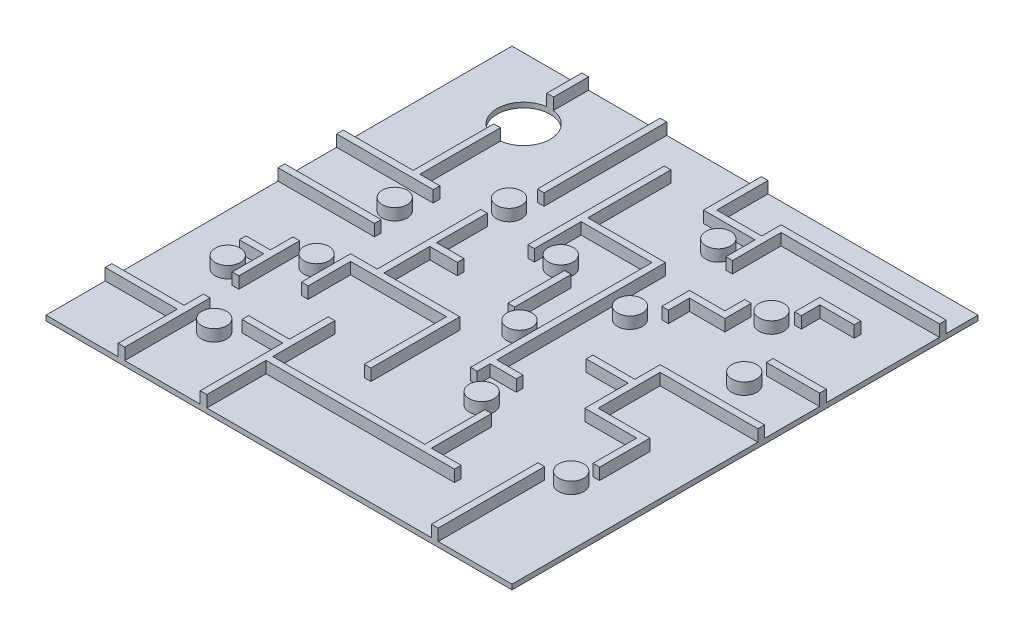
SolidWorks part; units mm, degrees
ref_plane "Front Plane" through (0, 0, 0) normal (0, 0, 1) x (1, 0, 0)
ref_plane "Top Plane" through (0, 0, 0) normal (0, 1, 0) x (1, 0, 0)
ref_plane "Right Plane" through (0, 0, 0) normal (1, 0, 0) x (0, 0, -1)
sketch "Sketch1" plane through (0, 0, 0) normal (0, 1, 0) x (1, 0, 0)
  line L1 (140, -140) -> (-140, -140)
  line L2 (140, -140) -> (140, 140)
  line L3 (140, 140) -> (-140, 140)
  line L4 (-140, -140) -> (-140, 140)
  line L5 (140, -140) -> (-140, 140) construction
  line L6 (140, 140) -> (-140, -140) construction
  circle A0 centre (-96, 103) radius 12.5 construction
  circle A2 centre (-96, 103) radius 16
  point P0 (0, 0)
  dimension "D2" = 25
  dimension "D4" = 44
  dimension "D5" = 37
  dimension "D3" = 32
  dimension "D1" = 280
extrude "Boss-Extrude1" add sketch "Sketch1" along normal mid plane 3
sketch "Sketch2" plane through (0, 1.5, 0) normal (0, 1, 0) x (1, 0, 0)
  line L0 (-139.5466, -22.5168) -> (140.7215, -22.5168) construction
  line L1 (-51, 140) -> (-51, 66.2868)
  line L5 (-140, 140) -> (-140, -140)
  line L6 (-140, -140) -> (140, -140)
  line L7 (140, -140) -> (140, 140)
  line L8 (140, 140) -> (-140, 140)
  line L9 (-140, 140) -> (-140, -140) construction
  line L10 (-140, -140) -> (140, -140) construction
  line L11 (140, -140) -> (140, 140) construction
  line L12 (140, 140) -> (-140, 140) construction
  line L14 (-82, 34.6244) -> (-82, 3.4233) construction
  line L16 (-94, 140) -> (-98, 140)
  line L17 (-94, 140) -> (-94, 118.8745)
  line L19 (-98, 140) -> (-98, 118.8745)
  line L20 (-94, 140) -> (-98, 118.8745) construction
  line L21 (-94, 118.8745) -> (-98, 140) construction
  line L22 (-51, 66.2868) -> (-47, 66.2868)
  line L25 (-47, 66.2868) -> (-47, 140)
  line L26 (-47, 140) -> (-51, 140)
  line L27 (-140, 38.6244) -> (-98, 38.6244)
  line L29 (-98, 38.6244) -> (-98, 87.1255)
  line L31 (-94, 38.6244) -> (-94, 87.1255)
  line L32 (-98, 38.6244) -> (-94, 87.1255) construction
  line L33 (-98, 87.1255) -> (-94, 38.6244) construction
  line L34 (-94, 38.6244) -> (-82, 38.6244)
  line L35 (-82, 38.6244) -> (-82, 34.6244)
  line L36 (-82, 34.6244) -> (-140, 34.6244)
  line L37 (-140, 34.6244) -> (-140, 38.6244)
  line L38 (-140, -100.4184) -> (-96.6685, -100.4184)
  line L39 (-140, 3.4233) -> (-82, 3.4233)
  line L40 (-140, 3.4233) -> (-140, -0.5767)
  line L41 (-140, -0.5767) -> (-82, -0.5767)
  line L42 (-82, 3.4233) -> (-82, -0.5767)
  line L43 (-96.6685, -100.4184) -> (-96.6685, -88.7386)
  line L44 (-96.6685, -88.7386) -> (-92.6685, -88.7386)
  line L45 (-92.6685, -88.7386) -> (-92.6685, -140)
  line L46 (-92.6685, -140) -> (-96.6685, -140)
  line L47 (-96.6685, -140) -> (-96.6685, -104.4184)
  line L48 (-96.6685, -104.4184) -> (-140, -104.4184)
  line L49 (-140, -104.4184) -> (-140, -100.4184)
  line L50 (-47.3451, -140) -> (-47.3451, -90.3646)
  line L51 (-47.3451, -90.3646) -> (-71.8819, -90.3646)
  line L52 (-71.8819, -90.3646) -> (-71.8819, -86.3646)
  line L53 (-71.8819, -86.3646) -> (-47.3451, -86.3646)
  line L54 (-47.3451, -86.3646) -> (-47.3451, -63.0886)
  line L55 (-47.3451, -63.0886) -> (-43.3451, -63.0886)
  line L56 (-43.3451, -63.0886) -> (-43.3451, -100.4184)
  line L57 (-43.3451, -100.4184) -> (48.0278, -100.4184)
  line L58 (48.0278, -100.4184) -> (48.0278, -64.3719)
  line L59 (48.0278, -64.3719) -> (52.0278, -64.3719)
  line L60 (52.0278, -64.3719) -> (52.0278, -100.4184)
  line L61 (52.0278, -100.4184) -> (69.8279, -100.4184)
  line L62 (69.8279, -100.4184) -> (69.8279, -104.4184)
  line L63 (69.8279, -104.4184) -> (-43.3451, -104.4184)
  line L64 (-43.3451, -104.4184) -> (-43.3451, -140)
  line L65 (-43.3451, -140) -> (-47.3451, -140)
  line L66 (140, 7.7373) -> (81.2931, 7.7373)
  line L67 (91.6226, -76) -> (95.6226, -76)
  line L68 (91.6226, -76) -> (91.6226, -140)
  line L69 (91.6226, -140) -> (95.6226, -140)
  line L70 (95.6226, -76) -> (95.6226, -140)
  line L71 (81.2931, 7.7373) -> (81.2931, -29.5435)
  line L72 (81.2931, -29.5435) -> (112.4312, -29.5435)
  line L73 (112.4312, -29.5435) -> (112.4312, -59.7773)
  line L74 (112.4312, -59.7773) -> (108.4312, -59.7773)
  line L75 (108.4312, -59.7773) -> (108.4312, -33.5435)
  line L76 (108.4312, -33.5435) -> (77.2931, -33.5435)
  line L77 (77.2931, -33.5435) -> (77.2931, -7.4768)
  line L78 (77.2931, -7.4768) -> (52.0278, -7.4768)
  line L79 (52.0278, -7.4768) -> (52.0278, -3.4768)
  line L80 (52.0278, -3.4768) -> (77.2931, -3.4768)
  line L81 (77.2931, -3.4768) -> (77.2931, 11.7373)
  line L82 (77.2931, 11.7373) -> (140, 11.7373)
  line L83 (140, 11.7373) -> (140, 7.7373)
  line L84 (-99.5107, -32.1119) -> (-95.5107, -32.1119)
  line L85 (140, 48.844) -> (108, 48.844)
  line L86 (140, 48.844) -> (140, 44.844)
  line L87 (140, 44.844) -> (108, 44.844)
  line L88 (108, 48.844) -> (108, 44.844)
  line L89 (-95.5107, -32.1119) -> (-95.5107, -68.5942)
  line L90 (-95.5107, -68.5942) -> (-99.5107, -68.5942)
  line L91 (-99.5107, -68.5942) -> (-99.5107, -49.6758)
  line L92 (-99.5107, -49.6758) -> (-114.1271, -49.6758)
  line L93 (-114.1271, -49.6758) -> (-114.1271, -45.6758)
  line L94 (-114.1271, -45.6758) -> (-99.5107, -45.6758)
  line L95 (-99.5107, -45.6758) -> (-99.5107, -32.1119)
  line L96 (-73.4352, -53.0425) -> (-69.4352, -53.0425)
  line L97 (-69.4352, -53.0425) -> (-69.4352, -27.5282)
  line L98 (-69.4352, -27.5282) -> (-11.8371, -27.5282)
  line L99 (-11.8371, -27.5282) -> (-11.8371, -76.9197)
  line L100 (-11.8371, -76.9197) -> (-7.8371, -76.9197)
  line L101 (-7.8371, -76.9197) -> (-7.8371, -23.5282)
  line L102 (-7.8371, -23.5282) -> (-53.4401, -23.5282)
  line L103 (-53.4401, -23.5282) -> (-53.4401, 4.0431)
  line L104 (-53.4401, 4.0431) -> (-36.8827, 4.0431)
  line L105 (-36.8827, 4.0431) -> (-36.8827, 8.0431)
  line L106 (-36.8827, 8.0431) -> (-53.4401, 8.0431)
  line L107 (-53.4401, 8.0431) -> (-53.4401, 38.6312)
  line L108 (-53.4401, 38.6312) -> (-57.4401, 38.6312)
  line L109 (-57.4401, 38.6312) -> (-57.4401, -23.5282)
  line L110 (-57.4401, -23.5282) -> (-73.4352, -23.5282)
  line L111 (-73.4352, -23.5282) -> (-73.4352, -53.0425)
  line L112 (114.8331, 94.8013) -> (114.8331, 90.8013)
  line L113 (-0.421, 32.0095) -> (3.579, 32.0095)
  line L114 (-0.421, 32.0095) -> (-0.421, -1.9905)
  line L115 (-0.421, -1.9905) -> (3.579, -1.9905)
  line L116 (3.579, 32.0095) -> (3.579, -1.9905)
  line L117 (114.8331, 90.8013) -> (94.2035, 90.8013)
  line L118 (94.2035, 90.8013) -> (94.2035, 79.6255)
  line L119 (94.2035, 79.6255) -> (90.2035, 79.6255)
  line L120 (90.2035, 79.6255) -> (90.2035, 94.8013)
  line L121 (90.2035, 94.8013) -> (114.8331, 94.8013)
  line L122 (68.7421, 71) -> (68.7421, 59.1986)
  line L123 (68.7421, 59.1986) -> (47.4471, 59.1986)
  line L124 (47.4471, 59.1986) -> (47.4471, 42.5547)
  line L125 (47.4471, 42.5547) -> (51.4471, 42.5547)
  line L126 (51.4471, 42.5547) -> (51.4471, 55.1986)
  line L127 (51.4471, 55.1986) -> (72.7421, 55.1986)
  line L128 (72.7421, 55.1986) -> (72.7421, 71)
  line L129 (72.7421, 71) -> (68.7421, 71)
  line L130 (21.7271, -46.6316) -> (25.7271, -46.6316)
  line L131 (25.7271, -46.6316) -> (25.7271, -38.8445)
  line L132 (25.7271, -38.8445) -> (41.4595, -38.8445)
  line L133 (41.4595, -38.8445) -> (41.4595, -34.8445)
  line L134 (41.4595, -34.8445) -> (25.7271, -34.8445)
  line L135 (25.7271, -34.8445) -> (25.7271, 66.4202)
  line L136 (25.7271, 66.4202) -> (-20.8726, 66.4202)
  line L137 (-20.8726, 66.4202) -> (-20.8726, 116.3442)
  line L138 (-20.8726, 116.3442) -> (-24.8726, 116.3442)
  line L139 (-24.8726, 116.3442) -> (-24.8726, 34.358)
  line L140 (-24.8726, 34.358) -> (-20.8726, 34.358)
  line L141 (-20.8726, 34.358) -> (-20.8726, 62.4202)
  line L142 (-20.8726, 62.4202) -> (21.7271, 62.4202)
  line L143 (21.7271, 62.4202) -> (21.7271, -46.6316)
  line L144 (140, 116.8451) -> (44.8417, 116.8451)
  line L145 (44.8417, 116.8451) -> (44.8417, 87.6566)
  line L146 (44.8417, 87.6566) -> (40.8417, 87.6566)
  line L147 (40.8417, 87.6566) -> (40.8417, 105.182)
  line L148 (40.8417, 105.182) -> (9.8488, 105.182)
  line L149 (9.8488, 105.182) -> (9.8488, 140)
  line L150 (9.8488, 140) -> (13.8488, 140)
  line L151 (13.8488, 140) -> (13.8488, 109.182)
  line L152 (13.8488, 109.182) -> (40.8417, 109.182)
  line L153 (40.8417, 109.182) -> (40.8417, 120.8451)
  line L154 (40.8417, 120.8451) -> (140, 120.8451)
  line L155 (140, 120.8451) -> (140, 116.8451)
  circle A0 centre (-96, 103) radius 16 construction
  circle A1 centre (-96, 103) radius 16 construction
  arc A4 (-94, 118.8745) -> (-98, 118.8745) centre (-96, 103) ccw
  arc A5 (-94, 87.1255) -> (-98, 87.1255) centre (-96, 103) cw
  circle A6 centre (-54.759, 52.9828) radius 7.5
  circle A7 centre (-89.4735, 19.0238) radius 7.5
  circle A8 centre (-83.7389, -33.6905) radius 7.5
  circle A9 centre (-109.5163, -61.2699) radius 7.5
  circle A10 centre (-80.6927, -98.2301) radius 7.5
  circle A12 centre (37.5874, -55.832) radius 7.5
  circle A13 centre (105.9105, -70.3332) radius 7.5
  circle A14 centre (11.8193, -7.3525) radius 7.5
  circle A15 centre (-9.7559, 39.067) radius 7.5
  circle A16 centre (29.1701, 94.8013) radius 7.5
  circle A17 centre (82.6249, 73.2846) radius 7.5
  circle A18 centre (37.5874, 33.2669) radius 7.5
  circle A19 centre (106.2527, 33.2879) radius 7.5
  point P9 (-82, 19.0238)
  point P14 (-96, 129.4373)
  point P21 (-96, 62.8749)
  point P66 (93.6226, -76)
  dimension "D6" = 29
  dimension "D8" = 15
  dimension "D52" = 15
  dimension "D53" = 15
  dimension "D54" = 15
  dimension "D55" = 15
  dimension "D57" = 15
  dimension "D58" = 15
  dimension "D59" = 15
  dimension "D60" = 15
  dimension "D61" = 15
  dimension "D62" = 15
  dimension "D63" = 15
  dimension "D64" = 15
  dimension "D1" = 0
  dimension "D3" = 4
  dimension "D4" = 4
  dimension "D9" = 4
  dimension "D10" = 4
  dimension "D11" = 58
  dimension "D12" = 4
  dimension "D13" = 58
  dimension "D14" = 4
  dimension "D15" = 4
  dimension "D16" = 4
  dimension "D17" = 4
  dimension "D18" = 4
  dimension "D19" = 4
  dimension "D20" = 4
  dimension "D21" = 4
  dimension "D22" = 64
  dimension "D23" = 4
  dimension "D24" = 4
  dimension "D25" = 4
  dimension "D26" = 4
  dimension "D27" = 4
  dimension "D28" = 4
  dimension "D29" = 32
  dimension "D30" = 4
  dimension "D31" = 4
  dimension "D32" = 4
  dimension "D33" = 4
  dimension "D34" = 4
  dimension "D35" = 4
  dimension "D36" = 4
  dimension "D37" = 4
  dimension "D38" = 34
  dimension "D39" = 4
  dimension "D40" = 4
  dimension "D41" = 4
  dimension "D42" = 4
  dimension "D43" = 4
  dimension "D44" = 4
  dimension "D45" = 4
  dimension "D46" = 4
  dimension "D47" = 4
  dimension "D48" = 4
  dimension "D49" = 4
  dimension "D50" = 4
  dimension "D51" = 4
extrude "Boss-Extrude2" add sketch "Sketch2" along normal blind 7
sketch "Sketch4" plane through (0, 1.5, 0) normal (0, 1, 0) x (1, 0, 0)
  line L0 (-98, 140) -> (-140, 140) construction
  line L1 (-103.2689, 140) -> (-87.6691, 140)
  line L2 (-103.2689, 140) -> (-103.2689, 109.252)
  line L3 (-103.2689, 109.252) -> (-87.6691, 109.252)
  line L4 (-87.6691, 140) -> (-87.6691, 109.252)
  line L5 (5.9631, 143.7406) -> (7.9794, 102.774)
  line L6 (-145.5082, 88.7508) -> (-75.5684, 88.7508)
  line L7 (-145.5082, 88.7508) -> (-145.5082, 30.0852)
  line L8 (-145.5082, 30.0852) -> (-75.5684, 30.0852)
  line L9 (-75.5684, 88.7508) -> (-75.5684, 30.0852)
  line L10 (-62.1484, 143.7406) -> (-36.1488, 143.7406)
  line L11 (-62.1484, 143.7406) -> (-62.1484, 63.1419)
  line L12 (-62.1484, 63.1419) -> (-36.1488, 63.1419)
  line L13 (-36.1488, 143.7406) -> (-36.1488, 63.1419)
  line L14 (-147.4549, 7.7999) -> (-80.2273, 7.7999)
  line L15 (-147.4549, 7.7999) -> (-147.4549, -3.3428)
  line L16 (-147.4549, -3.3428) -> (-80.2273, -3.3428)
  line L17 (-80.2273, 7.7999) -> (-80.2273, -3.3428)
  line L18 (-147.4549, -83.9416) -> (-90.2557, -83.9416)
  line L19 (-147.4549, -83.9416) -> (-147.4549, -144.4835)
  line L20 (-147.4549, -144.4835) -> (-90.2557, -144.4835)
  line L21 (-90.2557, -83.9416) -> (-90.2557, -144.4835)
  line L22 (97.7216, -74.6829) -> (89.8032, -74.6829)
  line L23 (97.7216, -74.6829) -> (97.7216, -144.4835)
  line L24 (97.7216, -144.4835) -> (89.8032, -144.4835)
  line L25 (89.8032, -74.6829) -> (89.8032, -144.4835)
  line L26 (143.8995, -60.5264) -> (51.0585, -60.5264)
  line L27 (143.8995, -60.5264) -> (143.8995, 16.1793)
  line L28 (143.8995, 16.1793) -> (51.0585, 16.1793)
  line L29 (51.0585, -60.5264) -> (51.0585, 16.1793)
  line L30 (88.927, 78.8767) -> (116.5902, 78.8767)
  line L31 (88.927, 78.8767) -> (88.927, 97.3845)
  line L32 (88.927, 97.3845) -> (116.5902, 97.3845)
  line L33 (116.5902, 78.8767) -> (116.5902, 97.3845)
  line L34 (73.3744, 72.1075) -> (45.9857, 72.1075)
  line L35 (73.3744, 72.1075) -> (73.3744, 41.1619)
  line L36 (73.3744, 41.1619) -> (45.9857, 41.1619)
  line L37 (45.9857, 72.1075) -> (45.9857, 41.1619)
  line L38 (105.2092, 50.41) -> (142.3795, 50.41)
  line L39 (105.2092, 50.41) -> (105.2092, 43.6518)
  line L40 (105.2092, 43.6518) -> (142.3795, 43.6518)
  line L41 (142.3795, 50.41) -> (142.3795, 43.6518)
  line L42 (7.9794, 102.774) -> (36.2066, 102.774)
  line L43 (36.2066, 102.774) -> (36.2066, 85.384)
  line L44 (36.2066, 85.384) -> (47.7999, 85.384)
  line L45 (47.7999, 85.384) -> (47.7999, 114.3673)
  line L46 (47.7999, 114.3673) -> (142.3795, 114.3673)
  line L47 (142.3795, 114.3673) -> (142.3795, 146.3749)
  line L48 (142.3795, 146.3749) -> (5.9631, 143.7406)
  line L49 (45.9857, -63.0608) -> (55.6128, -63.0608)
  line L50 (55.6128, -63.0608) -> (55.6128, -94.5644)
  line L51 (55.6128, -94.5644) -> (73.3744, -98.5969)
  line L52 (73.3744, -98.5969) -> (71.3652, -107.4466)
  line L53 (71.3652, -107.4466) -> (-50.2392, -144.4835)
  line L54 (-50.2392, -144.4835) -> (-51.2032, -94.5644)
  line L55 (-51.2032, -94.5644) -> (-74.182, -91.5401)
  line L56 (-74.182, -91.5401) -> (-74.182, -83.9416)
  line L57 (-74.182, -83.9416) -> (-51.2032, -83.9416)
  line L58 (-51.2032, -83.9416) -> (-51.2032, -60.5264)
  line L59 (-51.2032, -60.5264) -> (-41.5994, -61.7904)
  line L60 (-41.5994, -61.7904) -> (-39.8871, -96.5806)
  line L61 (-39.8871, -96.5806) -> (42.0032, -96.5806)
  line L62 (42.0032, -96.5806) -> (45.9857, -63.0608)
  line L63 (-5.6302, -79.1855) -> (-16.4674, -79.1855)
  line L64 (-16.4674, -79.1855) -> (-16.4674, -32.0613)
  line L65 (-16.4674, -32.0613) -> (-66.3537, -32.0613)
  line L66 (-66.3537, -32.0613) -> (-66.3537, -52.7277)
  line L67 (-66.3537, -52.7277) -> (-69.4859, -55.8599)
  line L68 (-69.4859, -55.8599) -> (-74.182, -55.8599)
  line L69 (-74.182, -55.8599) -> (-74.182, -19.9639)
  line L70 (-74.182, -19.9639) -> (-60.8244, -19.9639)
  line L71 (-60.8244, -19.9639) -> (-60.8244, 41.1619)
  line L72 (-60.8244, 41.1619) -> (-50.7212, 41.1619)
  line L73 (-50.7212, 41.1619) -> (-5.6302, -25.2565)
  line L74 (-5.6302, -25.2565) -> (-5.6302, -79.1855)
  line L75 (-95.4557, -29.8902) -> (-93.4806, -70.0213)
  line L76 (-93.4806, -70.0213) -> (-101.149, -70.0213)
  line L77 (-101.149, -70.0213) -> (-101.149, -52.7277)
  line L78 (-101.149, -52.7277) -> (-115.689, -51.0001)
  line L79 (-115.689, -51.0001) -> (-115.689, -42.3945)
  line L80 (-115.689, -42.3945) -> (-103.4173, -42.3945)
  line L81 (-103.4173, -42.3945) -> (-101.9316, -29.8902)
  line L82 (-101.9316, -29.8902) -> (-95.4557, -29.8902)
  line L83 (-28.4925, 119.5346) -> (-16.4674, 117.756)
  line L84 (-1.8935, 32.9846) -> (4.3847, 32.9846)
  line L85 (-1.8935, 32.9846) -> (-1.8935, -2.8259)
  line L86 (-1.8935, -2.8259) -> (4.3847, -2.8259)
  line L87 (4.3847, 32.9846) -> (4.3847, -2.8259)
  line L88 (-16.4674, 117.756) -> (-16.4674, 69.1408)
  line L89 (-16.4674, 69.1408) -> (27.2371, 69.1408)
  line L90 (27.2371, 69.1408) -> (27.2371, -32.0613)
  line L91 (27.2371, -32.0613) -> (45.9857, -32.0613)
  line L92 (45.9857, -32.0613) -> (43.134, -41.9421)
  line L93 (43.134, -41.9421) -> (27.2371, -41.9421)
  line L94 (27.2371, -41.9421) -> (27.2371, -51.0001)
  line L95 (27.2371, -51.0001) -> (17.9746, -49.6302)
  line L96 (17.9746, -49.6302) -> (19.7304, -15.8544)
  line L97 (19.7304, -15.8544) -> (20.3739, 2.1642)
  line L98 (20.3739, 2.1642) -> (18.5332, 38.2959)
  line L99 (18.5332, 38.2959) -> (-16.8954, 50.706)
  line L100 (-16.8954, 50.706) -> (-19.4975, 31.4904)
  line L101 (-19.4975, 31.4904) -> (-28.3046, 32.0909)
  line L102 (-28.3046, 32.0909) -> (-28.4925, 119.5346)
  line L104 (-67.0582, 61.2608) -> (-47.0319, 61.2608)
  line L105 (-67.0582, 61.2608) -> (-67.0582, 43.6518)
  line L106 (-67.0582, 43.6518) -> (-47.0319, 43.6518)
  line L107 (-47.0319, 61.2608) -> (-47.0319, 43.6518)
